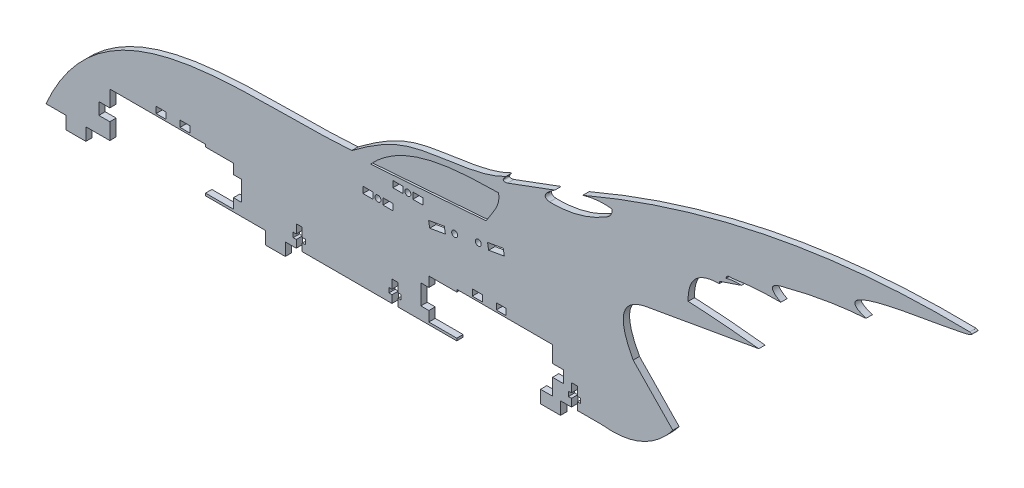
SolidWorks part; units mm, degrees
ref_plane "前视基准面" through (0, 0, 0) normal (0, 0, 1) x (1, 0, 0)
ref_plane "上视基准面" through (0, 0, 0) normal (0, 1, 0) x (1, 0, 0)
ref_plane "右视基准面" through (0, 0, 0) normal (1, 0, 0) x (0, 0, -1)
sketch "Sketch1" plane through (0, 0, 0) normal (0, 0, 1) x (1, 0, 0)
  line L0 (-360, 0) -> (360, 0) construction
  line L1 (-19.5671, 50.1455) -> (753.6757, 55.0373) construction
  line L2 (-32.114, 89.2833) -> (541.2194, 89.2833) construction
sketch "Sketch2" plane through (0, 0, 0) normal (0, 0, 1) x (1, 0, 0)
  line L0 (-171.469, -34.0766) -> (107.0727, -34.0766)
  spline S0 degree 2 poles (291.7809, 98.4714) (190.6089, 100.5394) (97.7379, 60.7759) knots 0 0 0 1 1 1
  spline S1 degree 2 poles (97.7379, 60.7759) (104.9288, 63.0011) (112.3796, 62.1565) knots 0 0 0 1 1 1
  spline S2 degree 2 poles (112.3796, 62.1565) (112.7301, 59.0518) (109.5504, 57.3117) knots 0 0 0 1 1 1
  spline S3 degree 2 poles (109.5504, 57.3117) (96.53, 49.2469) (81.0586, 49.5528) knots 0 0 0 1 1 1
  spline S4 degree 2 poles (81.0586, 49.5528) (75.6423, 50.628) (83.6966, 55.9983) knots 0 0 0 1 1 1
  spline S5 degree 1 poles (83.6966, 55.9983) (60.0234, 47.198) knots 0 0 1 1
  spline S6 degree 2 poles (60.0234, 47.198) (56.1503, 46.2452) (59.1238, 49.6133) knots 0 0 0 1 1 1
  spline S7 degree 3 poles (59.1238, 49.6133) (44.2925, 41.9215) (13.2093, 43.4053) (-7.7072, 29.9938) (-18.1066, 22.3013) knots 0 0 0 0 0.606339 1 1 1 1
  spline S8 degree 3 poles (-18.1066, 22.3013) (-73.3001, 18.1787) (-142.3815, 32.9288) (-171.469, -34.0766) knots 0 0 0 0 1 1 1 1
  spline S9 degree 2 poles (107.0727, -34.0766) (128.9682, -36.583) (142.8921, -18.7155) knots 0 0 0 1 1 1
  spline S10 degree 2 poles (166.2115, 56.6) (150.1116, 56.4482) (150.5886, 41.1327) knots 0 0 0 1 1 1
  spline S11 degree 2 poles (150.5886, 41.1327) (168.3325, 40.2418) (185.983, 38.2447) knots 0 0 0 1 1 1
  spline S12 degree 1 poles (185.983, 38.2447) (129.8121, 28.3469) knots 0 0 1 1
  spline S13 degree 2 poles (129.8121, 28.3469) (110.3675, 24.8357) (122.9996, 1.8225) knots 0 0 0 1 1 1
  spline S14 degree 1 poles (122.9996, 1.8225) (142.8921, -18.7155) knots 0 0 1 1
  spline S25 degree 1 poles (166.2115, 56.6) (166.2327, 57.6697) knots 0 0 1 1
  spline S26 degree 1 poles (166.2327, 57.6697) (177.2433, 61.4033) knots 0 0 1 1
  spline S27 degree 2 poles (177.2433, 61.4033) (173.3395, 61.7966) (169.6271, 60.6108) knots 0 0 0 1 1 1
  spline S28 degree 2 poles (169.6271, 60.6108) (169.7629, 62.5449) (172.4023, 62.1565) knots 0 0 0 1 1 1
  spline S29 degree 2 poles (172.4023, 62.1565) (184.6173, 64.0415) (197.0298, 63.9473) knots 0 0 0 1 1 1
  spline S30 degree 2 poles (197.0298, 63.9473) (187.7347, 69.0696) (198.9644, 71.4021) knots 0 0 0 1 1 1
  spline S31 degree 2 poles (198.9644, 71.4021) (219.0035, 76.7865) (239.7646, 78.3299) knots 0 0 0 1 1 1
  spline S32 degree 3 poles (291.7809, 98.4714) (303.0909, 95.7177) (210.844, 88.0264) (239.7646, 78.3299) knots 0 0 0 0 1 1 1 1
extrude "Boss-Extrude1" add sketch "Sketch2" along normal blind 3.175
sketch "Sketch3" plane through (0, 0, 3.175) normal (0, 0, 1) x (1, 0, 0)
  line L0 (-156.469, -23.0187) -> (-156.469, -49.8356) construction
  line L1 (-161.469, -34.0766) -> (-151.469, -34.0766)
  line L2 (-171.469, -34.0766) -> (107.0727, -34.0766) construction
  line L3 (-161.469, -34.0766) -> (-161.469, -40.4266)
  line L4 (-161.469, -40.4266) -> (-151.469, -40.4266)
  line L5 (-151.469, -40.4266) -> (-151.469, -34.0766)
  line L6 (-106.469, -7.8183) -> (-106.469, -55.0925) construction
  line L7 (-56.469, -23.0187) -> (-56.469, -49.8356) construction
  line L8 (-61.469, -40.4266) -> (-61.469, -34.0766)
  line L9 (-51.469, -40.4266) -> (-61.469, -40.4266)
  line L10 (-51.469, -34.0766) -> (-51.469, -40.4266)
  line L11 (-51.469, -34.0766) -> (-61.469, -34.0766)
  line L12 (-37.469, -5.6354) -> (-37.469, -55.0925) construction
  line L13 (81.531, -23.0187) -> (81.531, -49.8356) construction
  line L14 (76.531, -40.4266) -> (76.531, -34.0766)
  line L15 (86.531, -40.4266) -> (76.531, -40.4266)
  line L16 (86.531, -34.0766) -> (86.531, -40.4266)
  line L17 (86.531, -34.0766) -> (76.531, -34.0766)
  point P6 (-156.469, -34.0766)
  dimension "D1" = 10
  dimension "D2" = 15
  dimension "D3" = 6.35
  dimension "D4" = 100
  dimension "D5" = 238
extrude "Boss-Extrude2" add sketch "Sketch3" against normal blind 3.175
sketch "Sketch4" plane through (0, 0, 3.175) normal (0, 0, 1) x (1, 0, 0)
  line L0 (-8.7353, 21.0767) -> (49.2725, 25.4437)
  spline S0 degree 3 poles (55.4358, 40.7209) (33.0546, 40.3601) (7.8741, 39.273) (-8.7353, 21.0767) knots 0 0 0 0 1 1 1 1
  spline S1 degree 3 poles (55.4358, 40.7209) (56.7107, 34.9555) (51.7522, 29.9519) (49.2725, 25.4437) knots 0 0 0 0 1 1 1 1
extrude "Cut-Extrude1" cut sketch "Sketch4" against normal blind 1
sketch "Sketch5" plane through (0, 0, 3.175) normal (0, 0, 1) x (1, 0, 0)
  line L0 (-44.469, -4.9545) -> (-44.469, -56.9042) construction
  line L1 (-45.969, -34.0766) -> (-42.969, -34.0766)
  line L2 (-151.469, -34.0766) -> (-61.469, -34.0766) construction
  line L3 (-45.969, -34.0766) -> (-45.969, -30.2766)
  line L4 (-45.969, -23.4266) -> (-42.969, -23.4266)
  line L5 (-42.969, -23.4266) -> (-42.969, -27.8766)
  line L6 (-161.469, -40.4266) -> (-151.469, -40.4266) construction
  line L7 (-41.419, -27.8766) -> (-41.419, -30.2766)
  line L8 (-47.519, -27.8766) -> (-47.519, -30.2766)
  line L9 (-47.519, -27.8766) -> (-45.969, -27.8766)
  line L10 (-47.519, -30.2766) -> (-45.969, -30.2766)
  line L11 (-47.519, -29.0766) -> (-93.8427, -29.0766) construction
  line L12 (-161.469, -34.0766) -> (-161.469, -40.4266) construction
  line L13 (-42.969, -27.8766) -> (-41.419, -27.8766)
  line L14 (-42.969, -30.2766) -> (-41.419, -30.2766)
  line L15 (-45.969, -27.8766) -> (-45.969, -23.4266)
  line L16 (-42.969, -30.2766) -> (-42.969, -34.0766)
  line L17 (-20.469, -10.7451) -> (-20.469, -65.5516) construction
  line L18 (3.531, -4.9545) -> (3.531, -56.9042) construction
  line L19 (2.031, -30.2766) -> (2.031, -34.0766)
  line L20 (5.031, -27.8766) -> (5.031, -23.4266)
  line L21 (2.031, -30.2766) -> (0.481, -30.2766)
  line L22 (2.031, -27.8766) -> (0.481, -27.8766)
  line L23 (6.581, -30.2766) -> (5.031, -30.2766)
  line L24 (6.581, -27.8766) -> (5.031, -27.8766)
  line L25 (6.581, -27.8766) -> (6.581, -30.2766)
  line L26 (0.481, -27.8766) -> (0.481, -30.2766)
  line L27 (2.031, -23.4266) -> (2.031, -27.8766)
  line L28 (5.031, -23.4266) -> (2.031, -23.4266)
  line L29 (5.031, -34.0766) -> (5.031, -30.2766)
  line L30 (5.031, -34.0766) -> (2.031, -34.0766)
  line L31 (24.531, -8.6696) -> (24.531, -64.6722) construction
  line L32 (93.531, -4.9545) -> (93.531, -56.9042) construction
  line L33 (92.031, -30.2766) -> (92.031, -34.0766)
  line L34 (95.031, -27.8766) -> (95.031, -23.4266)
  line L35 (92.031, -30.2766) -> (90.481, -30.2766)
  line L36 (92.031, -27.8766) -> (90.481, -27.8766)
  line L37 (96.581, -30.2766) -> (95.031, -30.2766)
  line L38 (96.581, -27.8766) -> (95.031, -27.8766)
  line L39 (96.581, -27.8766) -> (96.581, -30.2766)
  line L40 (90.481, -27.8766) -> (90.481, -30.2766)
  line L41 (92.031, -23.4266) -> (92.031, -27.8766)
  line L42 (95.031, -23.4266) -> (92.031, -23.4266)
  line L43 (95.031, -34.0766) -> (95.031, -30.2766)
  line L44 (95.031, -34.0766) -> (92.031, -34.0766)
  point P6 (-44.469, -34.0766)
  dimension "D1" = 3
  dimension "D2" = 17
  dimension "D3" = 6.1
  dimension "D4" = 5
  dimension "D5" = 117
  dimension "D6" = 2.4
  dimension "D7" = 165
  dimension "D8" = 255
extrude "Cut-Extrude2" cut sketch "Sketch5" against normal through all
sketch "Sketch7" plane through (0, 0, 3.175) normal (0, 0, 1) x (1, 0, 0)
  line L0 (-91.469, -32.8766) -> (-77.469, -32.8766)
  line L1 (-139.469, -34.0766) -> (-139.469, -25.8766)
  line L2 (-151.469, -34.0766) -> (-61.469, -34.0766) construction
  line L3 (-139.469, -11.6766) -> (-91.469, -11.6766)
  line L4 (-91.469, -11.6766) -> (-91.469, -12.8766)
  line L5 (-139.469, -34.0766) -> (-91.469, -34.0766)
  line L6 (-155.6863, -22.8766) -> (-79.2758, -22.8766) construction
  line L7 (-91.469, -12.8766) -> (-77.469, -12.8766)
  line L8 (-77.469, -12.8766) -> (-77.469, -17.8766)
  line L9 (-91.469, -32.8766) -> (-91.469, -34.0766)
  line L10 (-139.469, -19.8766) -> (-144.969, -19.8766)
  line L11 (-139.469, -25.8766) -> (-144.969, -25.8766)
  line L12 (-144.969, -19.8766) -> (-144.969, -25.8766)
  line L13 (-139.469, -19.8766) -> (-139.469, -11.6766)
  line L14 (-77.469, -17.8766) -> (-73.469, -17.8766)
  line L15 (-77.469, -27.8766) -> (-73.469, -27.8766)
  line L16 (-73.469, -17.8766) -> (-73.469, -27.8766)
  line L17 (-77.469, -27.8766) -> (-77.469, -32.8766)
  line L18 (-28.469, 4.1122) -> (-28.469, -62.6854) construction
  line L19 (98.7482, -22.8766) -> (22.3377, -22.8766) construction
  line L20 (20.531, -27.8766) -> (20.531, -32.8766)
  line L21 (16.531, -17.8766) -> (16.531, -27.8766)
  line L22 (20.531, -27.8766) -> (16.531, -27.8766)
  line L23 (20.531, -17.8766) -> (16.531, -17.8766)
  line L24 (82.531, -19.8766) -> (82.531, -11.6766)
  line L25 (88.031, -19.8766) -> (88.031, -25.8766)
  line L26 (82.531, -25.8766) -> (88.031, -25.8766)
  line L27 (82.531, -19.8766) -> (88.031, -19.8766)
  line L28 (34.531, -32.8766) -> (34.531, -34.0766)
  line L29 (20.531, -12.8766) -> (20.531, -17.8766)
  line L30 (34.531, -12.8766) -> (20.531, -12.8766)
  line L31 (82.531, -34.0766) -> (34.531, -34.0766)
  line L32 (34.531, -11.6766) -> (34.531, -12.8766)
  line L33 (82.531, -11.6766) -> (34.531, -11.6766)
  line L34 (82.531, -34.0766) -> (82.531, -25.8766)
  line L35 (34.531, -32.8766) -> (20.531, -32.8766)
  line L36 (-120.2067, -9.1491) -> (-44.1643, -9.1491) construction
  line L37 (-107.769, -0.3828) -> (-107.769, -8.179) construction
  line L38 (-111.269, -10.7366) -> (-116.269, -10.7366)
  line L39 (-111.269, -10.7366) -> (-111.269, -7.5616)
  line L40 (-111.269, -7.5616) -> (-116.269, -7.5616)
  line L41 (-116.269, -10.7366) -> (-116.269, -7.5616)
  line L42 (-111.269, -10.7366) -> (-116.269, -7.5616) construction
  line L43 (-111.269, -7.5616) -> (-116.269, -10.7366) construction
  line L44 (-104.269, -7.5616) -> (-99.269, -10.7366) construction
  line L45 (-104.269, -10.7366) -> (-99.269, -7.5616) construction
  line L46 (-99.269, -10.7366) -> (-99.269, -7.5616)
  line L47 (-104.269, -7.5616) -> (-99.269, -7.5616)
  line L48 (-104.269, -10.7366) -> (-104.269, -7.5616)
  line L49 (-104.269, -10.7366) -> (-99.269, -10.7366)
  line L50 (47.331, -10.7366) -> (42.331, -7.5616) construction
  line L51 (47.331, -7.5616) -> (42.331, -10.7366) construction
  line L52 (54.331, -7.5616) -> (59.331, -10.7366) construction
  line L53 (54.331, -10.7366) -> (59.331, -7.5616) construction
  line L54 (47.331, -10.7366) -> (42.331, -10.7366)
  line L55 (47.331, -10.7366) -> (47.331, -7.5616)
  line L56 (47.331, -7.5616) -> (42.331, -7.5616)
  line L57 (42.331, -10.7366) -> (42.331, -7.5616)
  line L58 (59.331, -10.7366) -> (59.331, -7.5616)
  line L59 (54.331, -7.5616) -> (59.331, -7.5616)
  line L60 (54.331, -10.7366) -> (54.331, -7.5616)
  line L61 (54.331, -10.7366) -> (59.331, -10.7366)
  point P43 (-113.769, -9.1491)
  point P54 (-101.769, -9.1491)
  point P63 (44.831, -9.1491)
  point P64 (56.831, -9.1491)
  dimension "D3" = 48
  dimension "D1" = 32
  dimension "D2" = 22.4
  dimension "D4" = 20
  dimension "D5" = 14
  dimension "D6" = 6
  dimension "D7" = 5.5
  dimension "D8" = 4
  dimension "D9" = 10
  dimension "D10" = 90
  dimension "D11" = 12
  dimension "D12" = 23.2
  dimension "D13" = 0.94
  dimension "D14" = 3.175
  dimension "D15" = 5
extrude "Cut-Extrude3" cut sketch "Sketch7" against normal through all
sketch "Sketch8" plane through (0, 0, 3.175) normal (0, 0, 1) x (1, 0, 0)
  line L0 (0, 0) -> (0, 6) construction
  line L1 (0, 6) -> (50.4572, 14.897) construction
  line L2 (32.7597, 50.5612) -> (39.3923, 12.9459) construction
  line L3 (20.9566, 8.0832) -> (28.8351, 9.4724)
  line L4 (28.8351, 9.4724) -> (28.2838, 12.5992)
  line L5 (20.9566, 8.0832) -> (20.4053, 11.21)
  line L6 (20.4053, 11.21) -> (28.2838, 12.5992)
  line L7 (24.8959, 8.7778) -> (23.4697, 16.8657) construction
  line L8 (54.4401, 13.9873) -> (53.014, 22.0752) construction
  line L9 (57.828, 17.8086) -> (49.9495, 16.4194)
  line L10 (58.3793, 14.6819) -> (57.828, 17.8086)
  line L11 (50.5009, 13.2927) -> (49.9495, 16.4194)
  line L12 (58.3793, 14.6819) -> (50.5009, 13.2927)
  circle A0 centre (33.4835, 11.904) radius 1.5
  circle A1 centre (45.3012, 13.9878) radius 1.5
  point P8 (28.5594, 11.0358)
  dimension "D7" = 3
  dimension "D1" = 6
  dimension "D2" = 100
  dimension "D3" = 40
  dimension "D4" = 3.175
  dimension "D5" = 8
  dimension "D6" = 30
  dimension "D8" = 12
extrude "Cut-Extrude4" cut sketch "Sketch8" against normal through all
sketch "Sketch9" plane through (0, 0, 3.175) normal (0, 0, 1) x (1, 0, 0)
  line L0 (10, 32.0127) -> (10, 0) construction
  line L1 (-14.9157, 18) -> (23.6696, 18) construction
  line L2 (2.5, 19.5875) -> (7.5, 16.4125) construction
  line L3 (17.5, 16.4125) -> (12.5, 16.4125)
  line L4 (17.5, 16.4125) -> (17.5, 19.5875)
  line L5 (17.5, 19.5875) -> (12.5, 19.5875)
  line L6 (12.5, 16.4125) -> (12.5, 19.5875)
  line L7 (17.5, 16.4125) -> (12.5, 19.5875) construction
  line L8 (17.5, 19.5875) -> (12.5, 16.4125) construction
  line L9 (2.5, 16.4125) -> (7.5, 19.5875) construction
  line L10 (7.5, 16.4125) -> (7.5, 19.5875)
  line L11 (2.5, 19.5875) -> (7.5, 19.5875)
  line L12 (2.5, 16.4125) -> (2.5, 19.5875)
  line L13 (2.5, 16.4125) -> (7.5, 16.4125)
  line L14 (-5, 12.4125) -> (-5, -3.1137) construction
  line L15 (-20.9752, 8) -> (1.55, 8) construction
  line L17 (-12.5, 6.4125) -> (-7.5, 6.4125)
  line L18 (-12.5, 6.4125) -> (-12.5, 9.5875)
  line L19 (2.5, 6.4125) -> (-2.5, 9.5875) construction
  line L20 (-7.5, 6.4125) -> (-7.5, 9.5875)
  line L21 (-12.5, 9.5875) -> (-7.5, 6.4125) construction
  line L23 (-12.5, 9.5875) -> (-7.5, 9.5875)
  line L25 (2.5, 9.5875) -> (-2.5, 6.4125) construction
  line L26 (-12.5, 6.4125) -> (-7.5, 9.5875) construction
  line L28 (2.5, 9.5875) -> (-2.5, 9.5875)
  line L29 (-2.5, 6.4125) -> (-2.5, 9.5875)
  line L30 (2.5, 6.4125) -> (2.5, 9.5875)
  line L31 (2.5, 6.4125) -> (-2.5, 6.4125)
  circle A0 centre (10, 18) radius 1.5
  circle A1 centre (-5, 8) radius 1.5
  point P4 (15, 18)
  point P14 (5, 18)
  point P25 (0, 8)
  point P30 (-10, 8)
  point P34 (-12.5, 8)
  dimension "D6" = 3
  dimension "D7" = 8
  dimension "D12" = 3
  dimension "D1" = 10
  dimension "D2" = 18
  dimension "D3" = 3.175
  dimension "D4" = 5
  dimension "D5" = 5
  dimension "D8" = 5
  dimension "D9" = 5
  dimension "D10" = 3.175
  dimension "D11" = 10
extrude "Cut-Extrude5" cut sketch "Sketch9" against normal through all
